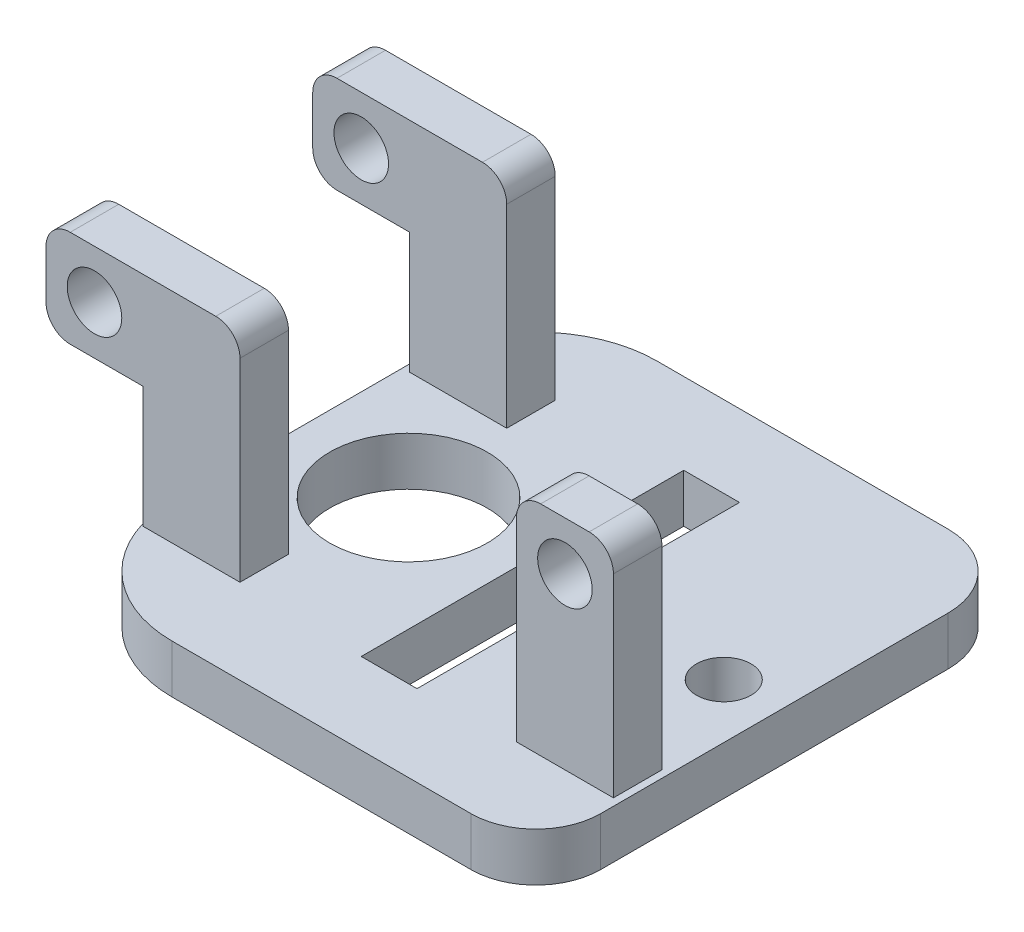
SolidWorks part; units mm, degrees
ref_plane "Front" through (0, 0, 0) normal (0, 0, 1) x (1, 0, 0)
ref_plane "Top" through (0, 0, 0) normal (0, 1, 0) x (1, 0, 0)
ref_plane "Right" through (0, 0, 0) normal (1, 0, 0) x (0, 0, -1)
sketch "Croquis1" plane through (0, 0, 0) normal (0, 1, 0) x (1, 0, 0)
  line L0 (-223.043, 0) -> (10929.1056, 0) construction
  line L1 (0, -223.043) -> (0, 10929.1056) construction
  line L2 (-223.043, -2.5) -> (10929.1056, -2.5) construction
  line L3 (-5, -10) -> (7.3263, -10)
  line L4 (-10, -5) -> (-10, 5)
  line L5 (-5, 10) -> (7, 10)
  line L6 (10, -7.3263) -> (10, 7)
  line L7 (-10, -10) -> (10, 10) construction
  line L8 (-10, 10) -> (10, -10) construction
  line L9 (-223.043, 2.5) -> (10929.1056, 2.5) construction
  line L11 (-0.55, -6.65) -> (1.75, -6.65)
  line L12 (-0.55, -6.65) -> (-0.55, 6.65)
  line L13 (-0.55, 6.65) -> (1.75, 6.65)
  line L14 (1.75, -6.65) -> (1.75, 6.65)
  line L15 (-0.55, -6.65) -> (1.75, 6.65) construction
  line L16 (-0.55, 6.65) -> (1.75, -6.65) construction
  arc A0 (-10, 5) -> (-5, 10) centre (-5, 5) cw
  arc A1 (-5, -10) -> (-10, -5) centre (-5, -5) cw
  arc A2 (10, 7) -> (7, 10) centre (7, 7) ccw
  arc A3 (10, -7.3263) -> (7.3263, -10) centre (7.3263, -7.3263) cw
  circle A4 centre (7.75, 0) radius 1.125
  circle A5 centre (7.75, 5) radius 1.125 construction
  circle A6 centre (7.75, -5) radius 1.125 construction
  circle A7 centre (-5.25, 0) radius 3.25
  point P4 (0, 0)
  point P32 (0.6, 0)
  dimension "D3" = 5
  dimension "D4" = 5
  dimension "D5" = 3
  dimension "D6" = 2.6737
  dimension "D7" = 2.25
  dimension "D8" = 2.25
  dimension "D14" = 6.5
  dimension "D15" = 4.75
  dimension "D1" = 20
  dimension "D2" = 20
  dimension "D11" = 13.3
  dimension "D12" = 2.3
  dimension "D13" = 6
  dimension "D9" = 2.5
  dimension "D10" = 2.5
extrude "Saliente-Extruir1" add sketch "Croquis1" along normal blind 2
sketch "Croquis2" plane through (0, 2, 0) normal (0, 1, 0) x (1, 0, 0)
  line L0 (0, -1000) -> (0, 49000) construction
  line L1 (-1000, 0) -> (49000, 0) construction
  line L2 (-1000, -6.5) -> (49000, -6.5) construction
  line L3 (-1000, 6.5) -> (49000, 6.5) construction
  line L4 (5, -1000) -> (5, 49000) construction
  line L5 (-7, -1000) -> (-7, 49000) construction
  line L6 (-9.7, 6.5) -> (-5.7, 6.5)
  line L7 (-5.7, 6.5) -> (-5.7, 4.5)
  line L8 (-5.7, 4.5) -> (-9.7, 4.5)
  line L9 (-9.7, 4.5) -> (-9.7, 6.5)
  line L10 (-9.7, -4.5) -> (-9.7, -6.5)
  line L11 (-5.7, -4.5) -> (-9.7, -4.5)
  line L12 (-5.7, -6.5) -> (-5.7, -4.5)
  line L13 (-9.7, -6.5) -> (-5.7, -6.5)
  line L14 (9.7, -4.5) -> (9.7, -6.5)
  line L15 (9.7, -6.5) -> (5.7, -6.5)
  line L16 (5.7, -6.5) -> (5.7, -4.5)
  line L17 (5.7, -4.5) -> (9.7, -4.5)
  line L18 (-10, 5) -> (-10, -5) construction
  circle A0 centre (-5.25, 0) radius 3.5 construction
  point P16 (-7.7, 6.5)
  dimension "D8" = 7
  dimension "D9" = 4.75
  dimension "D5" = 4
  dimension "D6" = 2
  dimension "D7" = 5.7
  dimension "D1" = 6.5
  dimension "D2" = 6.5
  dimension "D3" = 5
  dimension "D4" = 7
extrude "Saliente-Extruir2" add sketch "Croquis2" along normal blind 9
sketch "Croquis3" plane through (0, 0, 6.5) normal (0, 0, 1) x (1, 0, 0)
  line L2 (0, -1000) -> (0, 49000) construction
  line L3 (5.7, 11) -> (9.7, 11) construction
  line L5 (5.7, 11) -> (5.7, 2) construction
  circle A1 centre (7.7, 9) radius 1.125
  dimension "D1" = 2
  dimension "D2" = 2
extrude "Cortar-Extruir1" cut sketch "Croquis3" against normal up to surface (13 mm away) up to face at (-7.7, 6.5, -6.5)
sketch "Croquis4" plane through (0, 0, 6.5) normal (0, 0, 1) x (1, 0, 0)
  line L0 (-7.7, -993) -> (-7.7, 49007) construction
  line L1 (-9.7, 11) -> (-5.7, 11) construction
  line L2 (-1007.7153, 9.45) -> (48992.2847, 9.45) construction
  line L4 (-5.7, 11) -> (-5.7, 2) construction
  line L5 (-9.7, 11) -> (-5.7, 11)
  line L6 (-9.7, 11) -> (-9.7, 9.45)
  line L7 (-9.7, 9.45) -> (-5.7, 9.45)
  line L8 (-5.7, 11) -> (-5.7, 9.45)
  point P5 (-7.7, 11)
  dimension "D1" = 1.55
extrude "Cortar-Extruir2" [suppressed] cut sketch "Croquis4" against normal up to surface (13 mm away)
fillet "Redondeo1" [suppressed] radius 2
sketch "Croquis5" plane through (-9.7, 0, 0) normal (-1, 0, 0) x (0, 0, 1)
  line L0 (6.5, 11) -> (6.5, 2) construction
  line L1 (4.5, 11) -> (6.5, 11)
  line L2 (4.5, 11) -> (4.5, 7)
  line L3 (4.5, 7) -> (6.5, 7)
  line L4 (6.5, 11) -> (6.5, 7)
  line L5 (0, -1000) -> (0, 49000) construction
  line L6 (-5, 0) -> (5, 0) construction
  line L7 (-4.5, 11) -> (-4.5, 7)
  line L8 (-4.5, 7) -> (-6.5, 7)
  line L9 (-6.5, 11) -> (-6.5, 7)
  line L10 (-4.5, 11) -> (-6.5, 11)
  point P12 (0, 0)
  dimension "D1" = 4
extrude "Saliente-Extruir3" add sketch "Croquis5" along normal blind 4
sketch "Croquis6" plane through (0, 0, 6.5) normal (0, 0, 1) x (1, 0, 0)
  line L0 (-9.7, 7) -> (-13.7, 11) construction
  line L1 (-13.7, 7) -> (-9.7, 11) construction
  line L2 (-13.7, 11) -> (-5.7, 11) construction
  circle A0 centre (-11.7, 9) radius 1.125
  dimension "D1" = 2.25
extrude "Cortar-Extruir3" cut sketch "Croquis6" against normal through all
fillet "Redondeo2" radius 1 8 edges at (-13.7, 11, -5.5) (-13.7, 7, -5.5) (-13.7, 11, 5.5) (-13.7, 7, 5.5) (-5.7, 11, -5.5) (9.7, 11, 5.5) (5.7, 11, 5.5) (-5.7, 11, 5.5)
